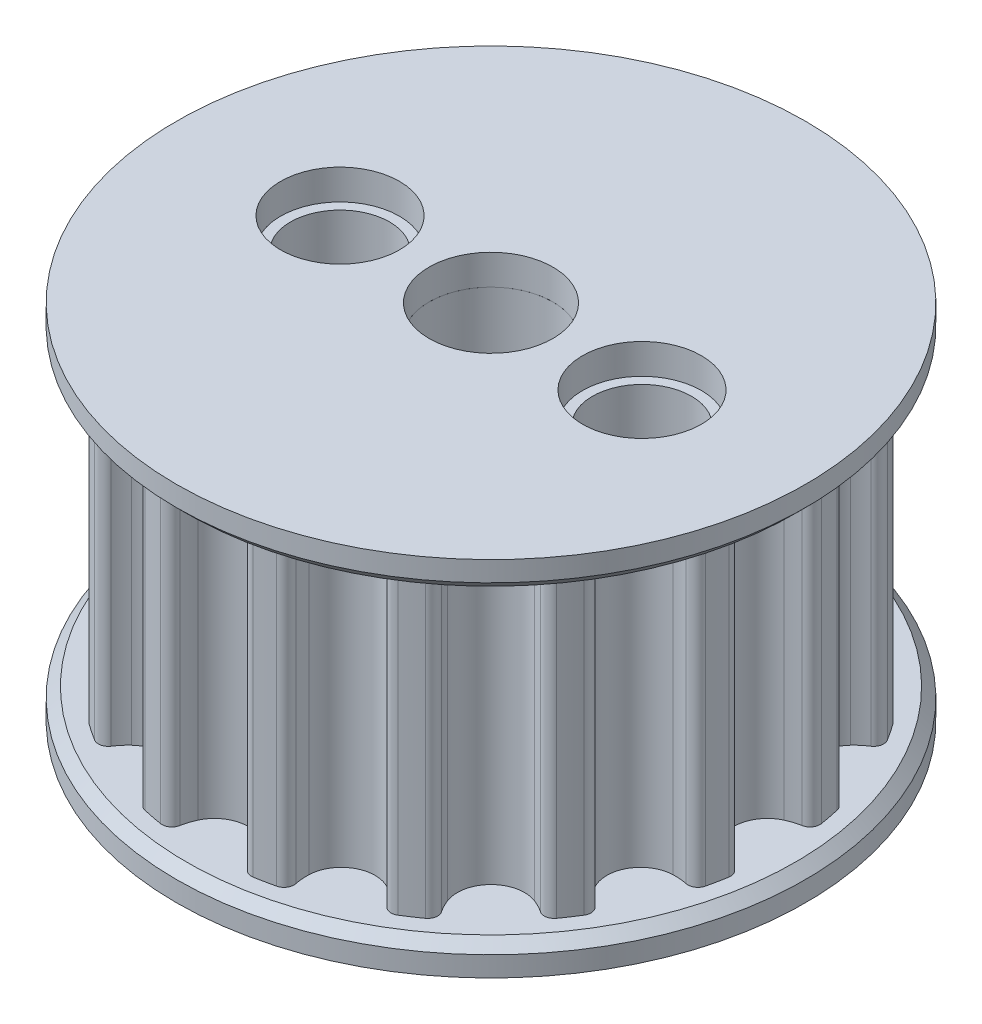
SolidWorks part; units mm, degrees
material "Alum Plate"
ref_plane "Front Plane" through (0, 0, 0) normal (0, 0, 1) x (1, 0, 0)
ref_plane "Top Plane" through (0, 0, 0) normal (0, 1, 0) x (1, 0, 0)
ref_plane "Right Plane" through (0, 0, 0) normal (1, 0, 0) x (0, 0, -1)
other "Bounding Box"
ref_plane "Default Plane" through (-8.9266, -12.7485, 0) normal (-0.1736, 0.9848, 0) x (0.9848, 0.1736, 0)
sketch "Sketch1" plane through (0, 0, 0) normal (0, 1, 0) x (1, 0, 0)
  line L0 (0, -7.8245) -> (0, 0) construction
  circle A0 centre (0, 0) radius 1.5625
  arc B0 (-1.8508, -6.777) -> (-1.6633, -7.0715) centre (-1.6061, -6.8282) ccw
  arc B1 (-1.6633, -7.0715) -> (-1.1695, -7.1697) centre (0, 0) ccw
  arc B2 (-1.1695, -7.1697) -> (-0.8836, -6.9694) centre (-1.1292, -6.923) ccw
  arc B3 (-0.7739, -6.6229) -> (-0.8836, -6.9694) centre (0.61, -7.2516) ccw
  arc B4 (0.7739, -6.6229) -> (-0.7739, -6.6229) centre (0, -6.9745) ccw
  arc B5 (0.8836, -6.9694) -> (0.7739, -6.6229) centre (-0.61, -7.2516) ccw
  arc B6 (0.8836, -6.9694) -> (1.1695, -7.1697) centre (1.1292, -6.923) ccw
  arc B7 (1.1695, -7.1697) -> (1.6633, -7.0715) centre (0, 0) ccw
  arc B8 (1.6633, -7.0715) -> (1.8508, -6.777) centre (1.6061, -6.8282) ccw
  arc B9 (1.8195, -6.4149) -> (1.8508, -6.777) centre (3.3386, -6.4662) ccw
  arc B10 (3.2495, -5.8226) -> (1.8195, -6.4149) centre (2.669, -6.4436) ccw
  arc B11 (3.4834, -6.1008) -> (3.2495, -5.8226) centre (2.2115, -6.9331) ccw
  arc B12 (3.4834, -6.1008) -> (3.8242, -6.1764) centre (3.6926, -5.9639) ccw
  arc B13 (3.8242, -6.1764) -> (4.2428, -5.8967) centre (0, 0) ccw
  arc B14 (4.2428, -5.8967) -> (4.3033, -5.5529) centre (4.0968, -5.6938) ccw
  arc B15 (4.1359, -5.2303) -> (4.3033, -5.5529) centre (5.559, -4.6963) ccw
  arc B16 (5.2303, -4.1359) -> (4.1359, -5.2303) centre (4.9317, -4.9317) ccw
  arc B17 (5.5529, -4.3033) -> (5.2303, -4.1359) centre (4.6963, -5.559) ccw
  arc B18 (5.5529, -4.3033) -> (5.8967, -4.2428) centre (5.6938, -4.0968) ccw
  arc B19 (5.8967, -4.2428) -> (6.1764, -3.8242) centre (0, 0) ccw
  arc B20 (6.1764, -3.8242) -> (6.1008, -3.4834) centre (5.9639, -3.6926) ccw
  arc B21 (5.8226, -3.2495) -> (6.1008, -3.4834) centre (6.9331, -2.2115) ccw
  arc B22 (6.4149, -1.8195) -> (5.8226, -3.2495) centre (6.4436, -2.669) ccw
  arc B23 (6.777, -1.8508) -> (6.4149, -1.8195) centre (6.4662, -3.3386) ccw
  arc B24 (6.777, -1.8508) -> (7.0715, -1.6633) centre (6.8282, -1.6061) ccw
  arc B25 (7.0715, -1.6633) -> (7.1697, -1.1695) centre (0, 0) ccw
  arc B26 (7.1697, -1.1695) -> (6.9694, -0.8836) centre (6.923, -1.1292) ccw
  arc B27 (6.6229, -0.7739) -> (6.9694, -0.8836) centre (7.2516, 0.61) ccw
  arc B28 (6.6229, 0.7739) -> (6.6229, -0.7739) centre (6.9745, 0) ccw
  arc B29 (6.9694, 0.8836) -> (6.6229, 0.7739) centre (7.2516, -0.61) ccw
  arc B30 (6.9694, 0.8836) -> (7.1697, 1.1695) centre (6.923, 1.1292) ccw
  arc B31 (7.1697, 1.1695) -> (7.0715, 1.6633) centre (0, 0) ccw
  arc B32 (7.0715, 1.6633) -> (6.777, 1.8508) centre (6.8282, 1.6061) ccw
  arc B33 (6.4149, 1.8195) -> (6.777, 1.8508) centre (6.4662, 3.3386) ccw
  arc B34 (5.8226, 3.2495) -> (6.4149, 1.8195) centre (6.4436, 2.669) ccw
  arc B35 (6.1008, 3.4834) -> (5.8226, 3.2495) centre (6.9331, 2.2115) ccw
  arc B36 (6.1008, 3.4834) -> (6.1764, 3.8242) centre (5.9639, 3.6926) ccw
  arc B37 (6.1764, 3.8242) -> (5.8967, 4.2428) centre (0, 0) ccw
  arc B38 (5.8967, 4.2428) -> (5.5529, 4.3033) centre (5.6938, 4.0968) ccw
  arc B39 (5.2303, 4.1359) -> (5.5529, 4.3033) centre (4.6963, 5.559) ccw
  arc B40 (4.1359, 5.2303) -> (5.2303, 4.1359) centre (4.9317, 4.9317) ccw
  arc B41 (4.3033, 5.5529) -> (4.1359, 5.2303) centre (5.559, 4.6963) ccw
  arc B42 (4.3033, 5.5529) -> (4.2428, 5.8967) centre (4.0968, 5.6938) ccw
  arc B43 (4.2428, 5.8967) -> (3.8242, 6.1764) centre (0, 0) ccw
  arc B44 (3.8242, 6.1764) -> (3.4834, 6.1008) centre (3.6926, 5.9639) ccw
  arc B45 (3.2495, 5.8226) -> (3.4834, 6.1008) centre (2.2115, 6.9331) ccw
  arc B46 (1.8195, 6.4149) -> (3.2495, 5.8226) centre (2.669, 6.4436) ccw
  arc B47 (1.8508, 6.777) -> (1.8195, 6.4149) centre (3.3386, 6.4662) ccw
  arc B48 (1.8508, 6.777) -> (1.6633, 7.0715) centre (1.6061, 6.8282) ccw
  arc B49 (1.6633, 7.0715) -> (1.1695, 7.1697) centre (0, 0) ccw
  arc B50 (1.1695, 7.1697) -> (0.8836, 6.9694) centre (1.1292, 6.923) ccw
  arc B51 (0.7739, 6.6229) -> (0.8836, 6.9694) centre (-0.61, 7.2516) ccw
  arc B52 (-0.7739, 6.6229) -> (0.7739, 6.6229) centre (0, 6.9745) ccw
  arc B53 (-0.8836, 6.9694) -> (-0.7739, 6.6229) centre (0.61, 7.2516) ccw
  arc B54 (-0.8836, 6.9694) -> (-1.1695, 7.1697) centre (-1.1292, 6.923) ccw
  arc B55 (-1.1695, 7.1697) -> (-1.6633, 7.0715) centre (0, 0) ccw
  arc B56 (-1.6633, 7.0715) -> (-1.8508, 6.777) centre (-1.6061, 6.8282) ccw
  arc B57 (-1.8195, 6.4149) -> (-1.8508, 6.777) centre (-3.3386, 6.4662) ccw
  arc B58 (-3.2495, 5.8226) -> (-1.8195, 6.4149) centre (-2.669, 6.4436) ccw
  arc B59 (-3.4834, 6.1008) -> (-3.2495, 5.8226) centre (-2.2115, 6.9331) ccw
  arc B60 (-3.4834, 6.1008) -> (-3.8242, 6.1764) centre (-3.6926, 5.9639) ccw
  arc B61 (-3.8242, 6.1764) -> (-4.2428, 5.8967) centre (0, 0) ccw
  arc B62 (-4.2428, 5.8967) -> (-4.3033, 5.5529) centre (-4.0968, 5.6938) ccw
  arc B63 (-4.1359, 5.2303) -> (-4.3033, 5.5529) centre (-5.559, 4.6963) ccw
  arc B64 (-5.2303, 4.1359) -> (-4.1359, 5.2303) centre (-4.9317, 4.9317) ccw
  arc B65 (-5.5529, 4.3033) -> (-5.2303, 4.1359) centre (-4.6963, 5.559) ccw
  arc B66 (-5.5529, 4.3033) -> (-5.8967, 4.2428) centre (-5.6938, 4.0968) ccw
  arc B67 (-5.8967, 4.2428) -> (-6.1764, 3.8242) centre (0, 0) ccw
  arc B68 (-6.1764, 3.8242) -> (-6.1008, 3.4834) centre (-5.9639, 3.6926) ccw
  arc B69 (-5.8226, 3.2495) -> (-6.1008, 3.4834) centre (-6.9331, 2.2115) ccw
  arc B70 (-6.4149, 1.8195) -> (-5.8226, 3.2495) centre (-6.4436, 2.669) ccw
  arc B71 (-6.777, 1.8508) -> (-6.4149, 1.8195) centre (-6.4662, 3.3386) ccw
  arc B72 (-6.777, 1.8508) -> (-7.0715, 1.6633) centre (-6.8282, 1.6061) ccw
  arc B73 (-7.0715, 1.6633) -> (-7.1697, 1.1695) centre (0, 0) ccw
  arc B74 (-7.1697, 1.1695) -> (-6.9694, 0.8836) centre (-6.923, 1.1292) ccw
  arc B75 (-6.6229, 0.7739) -> (-6.9694, 0.8836) centre (-7.2516, -0.61) ccw
  arc B76 (-6.6229, -0.7739) -> (-6.6229, 0.7739) centre (-6.9745, 0) ccw
  arc B77 (-6.9694, -0.8836) -> (-6.6229, -0.7739) centre (-7.2516, 0.61) ccw
  arc B78 (-6.9694, -0.8836) -> (-7.1697, -1.1695) centre (-6.923, -1.1292) ccw
  arc B79 (-7.1697, -1.1695) -> (-7.0715, -1.6633) centre (0, 0) ccw
  arc B80 (-7.0715, -1.6633) -> (-6.777, -1.8508) centre (-6.8282, -1.6061) ccw
  arc B81 (-6.4149, -1.8195) -> (-6.777, -1.8508) centre (-6.4662, -3.3386) ccw
  arc B82 (-5.8226, -3.2495) -> (-6.4149, -1.8195) centre (-6.4436, -2.669) ccw
  arc B83 (-6.1008, -3.4834) -> (-5.8226, -3.2495) centre (-6.9331, -2.2115) ccw
  arc B84 (-6.1008, -3.4834) -> (-6.1764, -3.8242) centre (-5.9639, -3.6926) ccw
  arc B85 (-6.1764, -3.8242) -> (-5.8967, -4.2428) centre (0, 0) ccw
  arc B86 (-5.8967, -4.2428) -> (-5.5529, -4.3033) centre (-5.6938, -4.0968) ccw
  arc B87 (-5.2303, -4.1359) -> (-5.5529, -4.3033) centre (-4.6963, -5.559) ccw
  arc B88 (-4.1359, -5.2303) -> (-5.2303, -4.1359) centre (-4.9317, -4.9317) ccw
  arc B89 (-4.3033, -5.5529) -> (-4.1359, -5.2303) centre (-5.559, -4.6963) ccw
  arc B90 (-4.3033, -5.5529) -> (-4.2428, -5.8967) centre (-4.0968, -5.6938) ccw
  arc B91 (-4.2428, -5.8967) -> (-3.8242, -6.1764) centre (0, 0) ccw
  arc B92 (-3.8242, -6.1764) -> (-3.4834, -6.1008) centre (-3.6926, -5.9639) ccw
  arc B93 (-3.2495, -5.8226) -> (-3.4834, -6.1008) centre (-2.2115, -6.9331) ccw
  arc B94 (-1.8195, -6.4149) -> (-3.2495, -5.8226) centre (-2.669, -6.4436) ccw
  arc B95 (-1.8508, -6.777) -> (-1.8195, -6.4149) centre (-3.3386, -6.4662) ccw
sketch_block_instance "Block-GT2 16 Tooth Profile-1"
sketch_block "Block-GT2 16 Tooth Profile" parameters "D1"=2.1152
extrude "Boss-Extrude1" add sketch "Sketch1" along normal mid plane 7.62
sketch "Sketch2" plane through (0, -3.81, 0) normal (0, -1, 0) x (1, 0, 0)
  circle A0 centre (0, 0) radius 7.9375
  circle A1 centre (0, 0) radius 1.5625 construction
  circle A2 centre (0, 0) radius 1.5625
  dimension "D1" = 15.875
extrude "Boss-Extrude2" add sketch "Sketch2" along normal blind 0.762 separate body
sketch "Sketch3" plane through (0, -4.572, 0) normal (0, -1, 0) x (1, 0, 0)
  line L0 (0, 0) -> (3.81, 0) construction
  line L1 (0, 0) -> (-3.81, 0) construction
  circle A0 centre (-3.81, 0) radius 1.5
  circle A1 centre (3.81, 0) radius 1.5
  dimension "D1" = 3
  dimension "D2" = 3.81
extrude "Cut-Extrude1" cut sketch "Sketch3" against normal through all
sketch "Sketch4" plane through (0, -3.81, 0) normal (0, -1, 0) x (1, 0, 0)
  circle A0 centre (-3.81, 0) radius 1.25
  circle A1 centre (3.81, 0) radius 1.25
  dimension "D1" = 2.5
extrude "Cut-Extrude2" cut sketch "Sketch4" against normal through all
chamfer "Chamfer1" distance 0.254 angle 45 1 edges at (0, -3.81, -7.9375)
mirror "Mirror2" about plane through (0, 0, 0) normal (0, 1, 0) of bodies 107 105
